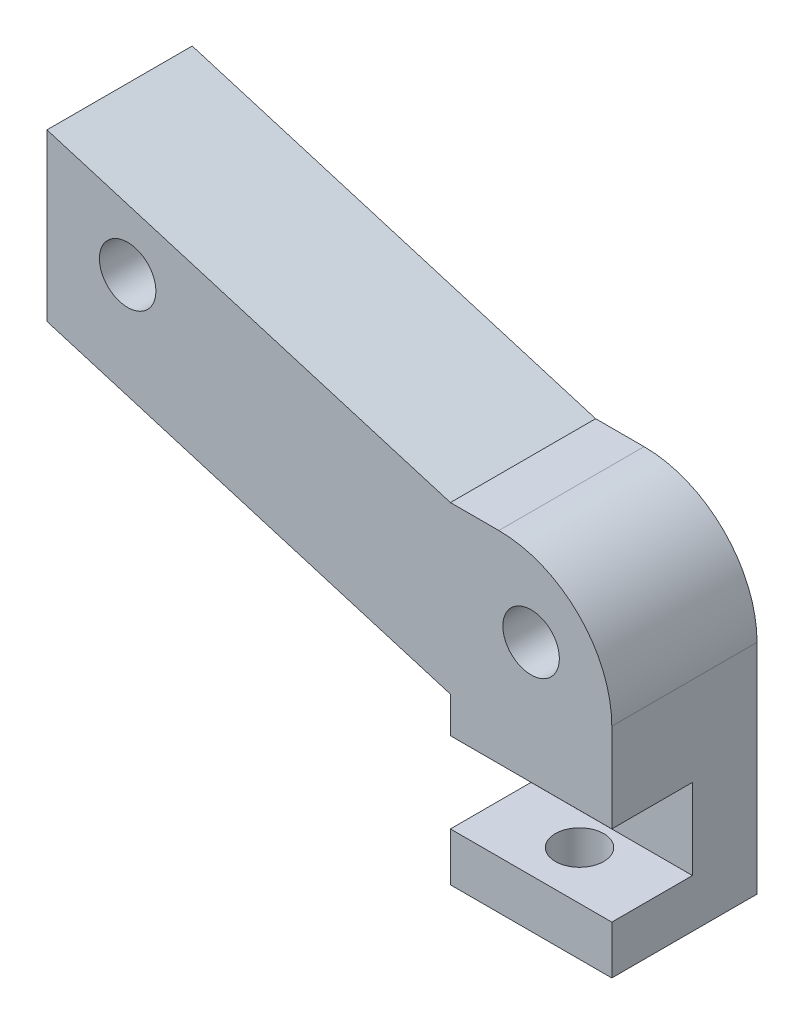
SolidWorks part; units mm, degrees
ref_plane "Front Plane" through (0, 0, 0) normal (0, 0, 1) x (1, 0, 0)
ref_plane "Top Plane" through (0, 0, 0) normal (0, 1, 0) x (1, 0, 0)
ref_plane "Right Plane" through (0, 0, 0) normal (1, 0, 0) x (0, 0, -1)
sketch "Sketch2" plane through (0, 0, 0) normal (0, 0, 1) x (1, 0, 0)
  line L0 (-15.8158, -97.1932) -> (-15.8158, -107.4744)
  line L1 (-15.8158, -97.1932) -> (9.1842, -104.6932)
  line L2 (-15.8158, -107.4744) -> (9.1842, -114.9744)
  line L8 (9.1842, -104.6932) -> (19.1842, -104.6932)
  line L9 (19.1842, -114.9744) -> (19.1842, -104.6932)
  line L12 (19.1842, -114.9744) -> (19.1842, -125.2065)
  line L13 (19.1842, -125.2065) -> (9.1842, -125.2065)
  line L14 (9.1842, -114.9744) -> (9.1842, -125.2065)
  dimension "D1" = 10
extrude "Boss-Extrude1" add sketch "Sketch2" along normal blind 9
sketch "Sketch3" plane through (0, 0, 9) normal (0, 0, 1) x (1, 0, 0)
  line L3 (19.1842, -125.2065) -> (19.1842, -104.6932) construction
  line L4 (-15.8158, -107.4744) -> (19.1842, -107.4744) construction
  circle A0 centre (14.1842, -109.6932) radius 1.75
  circle A1 centre (-10.8158, -102.4744) radius 1.75
extrude "Cut-Extrude1" cut sketch "Sketch3" against normal blind 9
sketch "Sketch5" plane through (0, -125.2065, 0) normal (0, -1, 0) x (1, 0, 0)
  line L0 (9.1842, 9) -> (9.1842, 0) construction
  line L2 (9.1842, 9) -> (19.1842, 9) construction
  circle A0 centre (14.1842, 6) radius 1.5
  dimension "D1" = 5
  dimension "D2" = 3
extrude "Cut-Extrude2" cut sketch "Sketch5" against normal blind 10 contours A0
sketch "Sketch6" plane through (19.1842, 0, 0) normal (1, 0, 0) x (0, 0, -1)
  line L0 (-9, -125.2065) -> (-9, -104.6932) construction
  line L1 (-9, -122.2065) -> (-4.0038, -122.2065)
  line L2 (-9, -122.2065) -> (-9, -117.2065)
  line L3 (-9, -117.2065) -> (-4.0038, -117.2065)
  line L4 (-4.0038, -122.2065) -> (-4.0038, -117.2065)
  line L5 (-9, -125.2065) -> (0, -125.2065) construction
  dimension "D1" = 3
  dimension "D2" = 5
extrude "Cut-Extrude3" cut sketch "Sketch6" against normal blind 10
fillet "Fillet1" radius 7 1 edges at (19.1842, -104.6932, 4.5)
